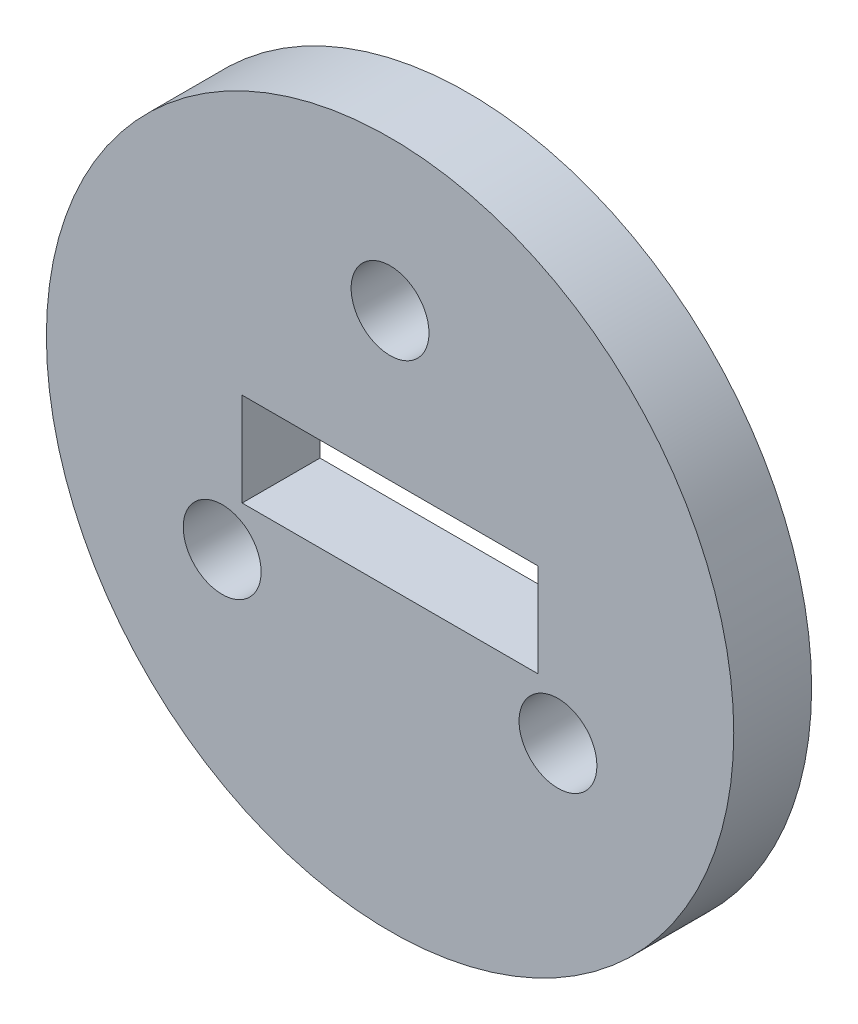
SolidWorks part; units mm, degrees
ref_plane "정면" through (0, 0, 0) normal (0, 0, 1) x (1, 0, 0)
ref_plane "윗면" through (0, 0, 0) normal (0, 1, 0) x (1, 0, 0)
ref_plane "우측면" through (0, 0, 0) normal (1, 0, 0) x (0, 0, -1)
sketch "스케치1" plane through (0, 0, 0) normal (0, 0, 1) x (1, 0, 0)
  line L0 (0, 0) -> (0, 33.5972) construction
  line L2 (-9.5, -3) -> (9.5, -3)
  line L3 (-9.5, -3) -> (-9.5, 3)
  line L4 (-9.5, 3) -> (9.5, 3)
  line L5 (9.5, -3) -> (9.5, 3)
  line L6 (-9.5, -3) -> (9.5, 3) construction
  line L7 (-9.5, 3) -> (9.5, -3) construction
  circle A0 centre (0, 0) radius 22.0716
  circle A1 centre (0, 12.45) radius 2.5
  circle A2 centre (0, 0) radius 15.95
  circle A3 centre (10.782, -6.225) radius 2.5
  circle A4 centre (-10.782, -6.225) radius 2.5
  point P14 (0, 0)
  dimension "D1" = 5
  dimension "D2" = 31.9
  dimension "D3" = 44.1433
  dimension "D4" = 12.45
  dimension "D7" = 6
  dimension "D8" = 19
  dimension "D5" = 3
extrude "보스-돌출1" add sketch "스케치1" along normal blind 5
